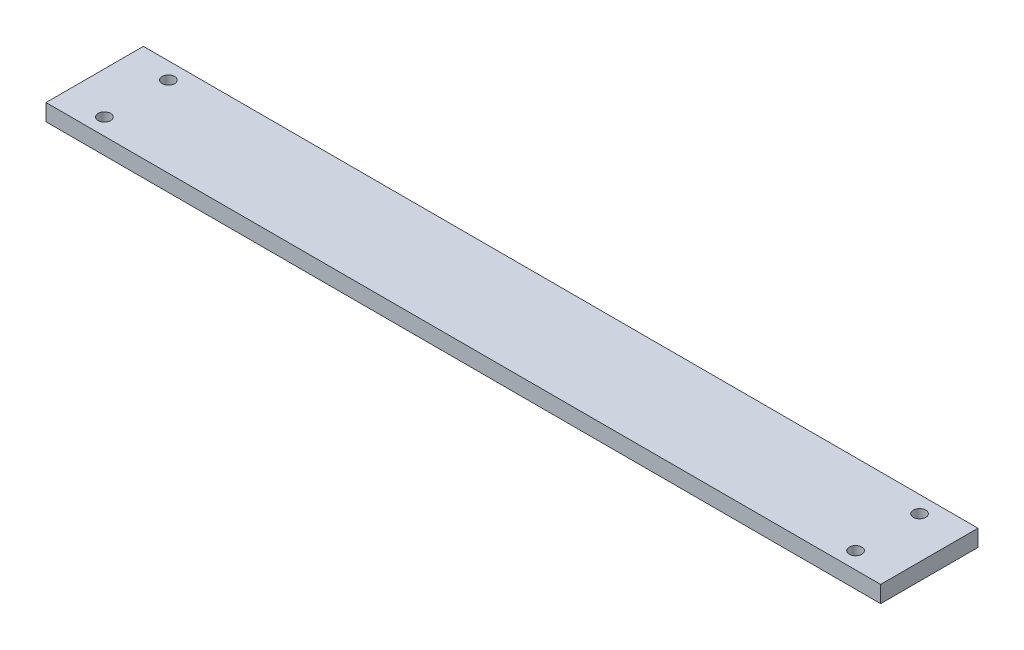
SolidWorks part; units mm, degrees
ref_plane "Front Plane" through (0, 0, 0) normal (0, 0, 1) x (1, 0, 0)
ref_plane "Top Plane" through (0, 0, 0) normal (0, 1, 0) x (1, 0, 0)
ref_plane "Right Plane" through (0, 0, 0) normal (1, 0, 0) x (0, 0, -1)
other "Configuration Table"
sketch "草图1" plane through (0, 0, 0) normal (0, 1, 0) x (1, 0, 0)
  line L1 (-300, -35) -> (300, -35)
  line L2 (-300, -35) -> (-300, 35)
  line L3 (-300, 35) -> (300, 35)
  line L4 (300, -35) -> (300, 35)
  line L5 (-300, -35) -> (300, 35) construction
  line L6 (-300, 35) -> (300, -35) construction
  circle A0 centre (-270, -23) radius 4.5
  circle A1 centre (-270, 23) radius 4.5
  circle A2 centre (270, -23) radius 4.5
  circle A3 centre (270, 23) radius 4.5
  point P0 (0, 0)
extrude "凸台-拉伸1" add sketch "草图1" along normal blind 12
